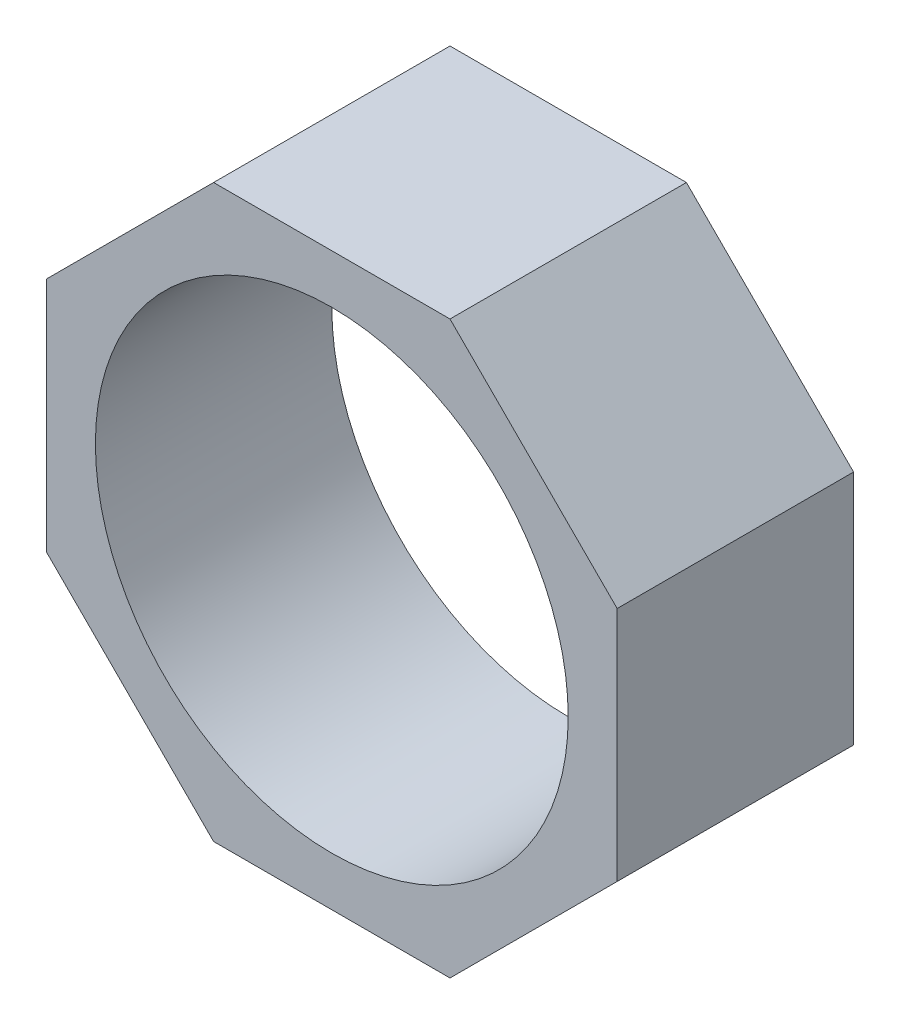
SolidWorks part; units mm, degrees
ref_plane "Front Plane" through (0, 0, 0) normal (0, 0, 1) x (1, 0, 0)
ref_plane "Top Plane" through (0, 0, 0) normal (0, 1, 0) x (1, 0, 0)
ref_plane "Right Plane" through (0, 0, 0) normal (1, 0, 0) x (0, 0, -1)
sketch "Sketch1" plane through (0, 0, 0) normal (0, 0, 1) x (1, 0, 0)
  line L0 (-1.25, 3.0178) -> (1.25, 3.0178)
  line L1 (1.25, 3.0178) -> (3.0178, 1.25)
  line L2 (3.0178, 1.25) -> (3.0178, -1.25)
  line L3 (3.0178, -1.25) -> (1.25, -3.0178)
  line L4 (1.25, -3.0178) -> (-1.25, -3.0178)
  line L5 (-1.25, -3.0178) -> (-3.0178, -1.25)
  line L6 (-3.0178, -1.25) -> (-3.0178, 1.25)
  line L7 (-3.0178, 1.25) -> (-1.25, 3.0178)
  line L8 (1.25, 3.0178) -> (-1.25, -3.0178) construction
  line L9 (-1.25, 3.0178) -> (1.25, -3.0178) construction
  circle A0 centre (0, 0) radius 2.5
  point P7 (0, 0)
  dimension "D1" = 5
  dimension "D2" = 2.5
extrude "Boss-Extrude1" add sketch "Sketch1" along normal blind 2.5
